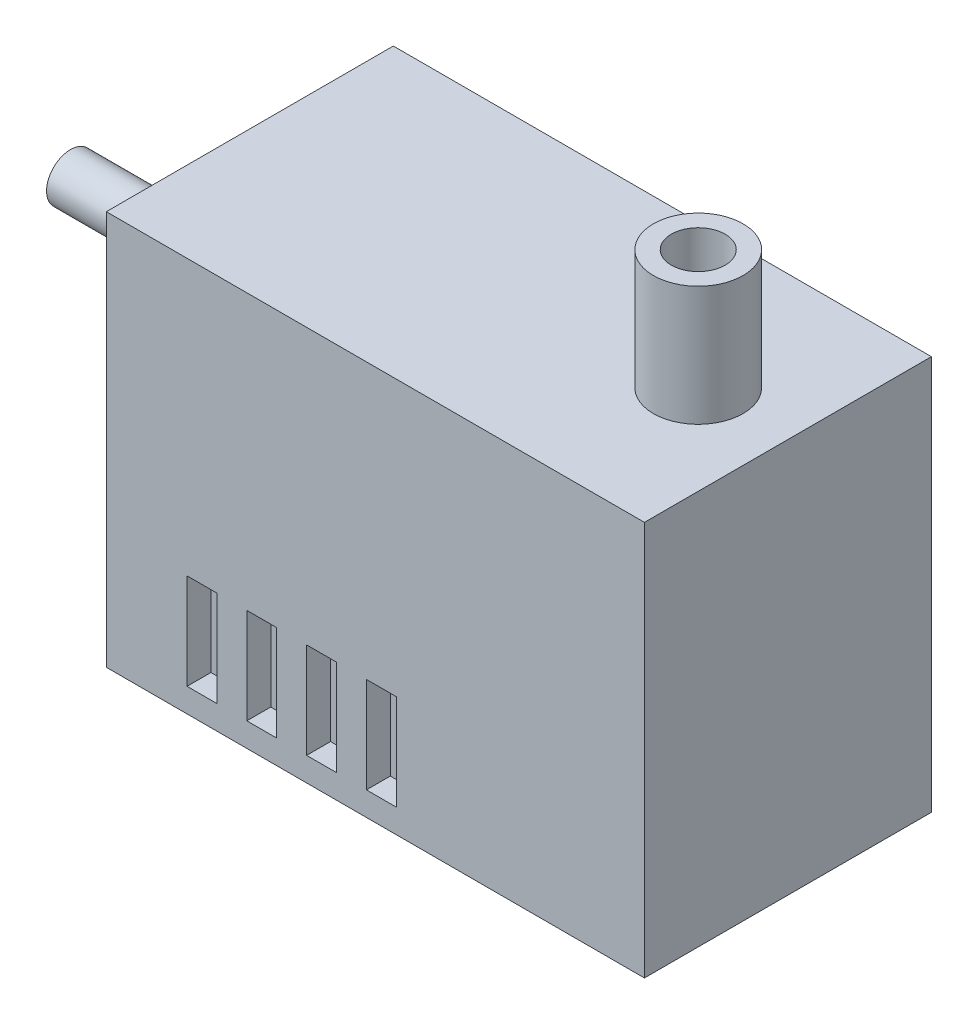
SolidWorks part; units mm, degrees
material "ABS"
ref_plane "Front Plane" through (0, 0, 0) normal (0, 0, 1) x (1, 0, 0)
ref_plane "Top Plane" through (0, 0, 0) normal (0, 1, 0) x (1, 0, 0)
ref_plane "Right Plane" through (0, 0, 0) normal (1, 0, 0) x (0, 0, -1)
other "Configuration Table"
sketch "Sketch1" plane through (0, 0, 0) normal (0, 1, 0) x (1, 0, 0)
  line L1 (-22.5, -12) -> (22.5, -12)
  line L2 (-22.5, -12) -> (-22.5, 12)
  line L3 (-22.5, 12) -> (22.5, 12)
  line L4 (22.5, -12) -> (22.5, 12)
  line L5 (-22.5, -12) -> (22.5, 12) construction
  line L6 (-22.5, 12) -> (22.5, -12) construction
  point P6 (0, 0)
  dimension "D1" = 45
  dimension "D2" = 24
extrude "Pump_Body" add sketch "Sketch1" along normal blind 33
sketch "Sketch2" plane through (0, 0, 0) normal (0, 1, 0) x (1, 0, 0)
  circle A0 centre (15, 0) radius 3.75
  dimension "D1" = 7.5
extrude "Outlet" add sketch "Sketch2" along normal blind 10 from offset 33
sketch "Sketch3" plane through (0, 0, 0) normal (0, 1, 0) x (1, 0, 0)
  circle A0 centre (15, 0) radius 2.25
  dimension "D1" = 4.5
extrude "Outlet_Bore" cut sketch "Sketch3" against normal blind 15 from offset 43
sketch "Sketch4" plane through (0, 0, 0) normal (0, 0, 1) x (1, 0, 0)
  line L0 (-15.75, 2) -> (-13.25, 2)
  line L1 (-13.25, 2) -> (-13.25, 10)
  line L2 (-13.25, 10) -> (-15.75, 10)
  line L3 (-15.75, 10) -> (-15.75, 2)
  line L4 (-10.75, 2) -> (-8.25, 2)
  line L5 (-8.25, 2) -> (-8.25, 10)
  line L6 (-8.25, 10) -> (-10.75, 10)
  line L7 (-10.75, 10) -> (-10.75, 2)
  line L8 (-5.75, 2) -> (-3.25, 2)
  line L9 (-3.25, 2) -> (-3.25, 10)
  line L10 (-3.25, 10) -> (-5.75, 10)
  line L11 (-5.75, 10) -> (-5.75, 2)
  line L12 (-0.75, 2) -> (1.75, 2)
  line L13 (1.75, 2) -> (1.75, 10)
  line L14 (1.75, 10) -> (-0.75, 10)
  line L15 (-0.75, 10) -> (-0.75, 2)
extrude "Inlet_Slots" cut sketch "Sketch4" against normal blind 2 from offset 12
sketch "Sketch5" plane through (0, 0, 0) normal (1, 0, 0) x (0, 0, -1)
  circle A0 centre (0, 22) radius 2
  dimension "D1" = 4
extrude "Cable_Stub" add sketch "Sketch5" along normal blind 15 from offset 37.5
equation "\"Jar_OD\"= 90  'ASSUMED - Part G fallback - jar outer diameter"
equation "\"Jar_H\"= 120  'ASSUMED - Part G fallback - jar height"
equation "\"Pump_L\"= 45  'ASSUMED - Part G fallback"
equation "\"Pump_W\"= 24  'ASSUMED - Part G fallback"
equation "\"Pump_H\"= 33  'ASSUMED - Part G fallback"
equation "\"Pump_Outlet_OD\"= 7.5  'ASSUMED - Part G fallback"
equation "\"Tube_OD\"= 8  'ASSUMED - Part G fallback"
equation "\"Tube_ID\"= 6  'ASSUMED - Part G fallback"
equation "\"TDS_Body_Dia\"= 12  'ASSUMED - Part G fallback"
equation "\"TDS_Wet_Len\"= 45  'ASSUMED - Part G fallback - length in water"
equation "\"DS_Tube_Dia\"= 6  'ASSUMED - Part G fallback"
equation "\"DS_Tube_Len\"= 50  'ASSUMED - Part G fallback"
equation "\"ORP_Body_Dia\"= 12  'ASSUMED - Part G fallback"
equation "\"ORP_Body_Len\"= 150  'ASSUMED - Part G fallback"
equation "\"ORP_Cap_Dia\"= 16  'ASSUMED - Part G fallback"
equation "\"Turb_W\"= 33  'ASSUMED - Part G fallback - head width"
equation "\"Turb_D\"= 28  'ASSUMED - Part G fallback - head depth"
equation "\"Turb_H\"= 30  'ASSUMED - Part G fallback - head height"
equation "\"Turb_Slot_W\"= 10  'ASSUMED - Part G fallback - slot width"
equation "\"Flow_L\"= 62  'ASSUMED - Part G fallback YF-S201"
equation "\"Flow_W\"= 36  'ASSUMED - Part G fallback"
equation "\"Flow_H\"= 35  'ASSUMED - Part G fallback"
equation "\"Thread_G12_OD\"= 20.955  'ASSUMED - Part G fallback thread G1/2 (major diameter)"
equation "\"Valve_L\"= 75  'ASSUMED - Part G fallback"
equation "\"Valve_W\"= 45  'ASSUMED - Part G fallback"
equation "\"Valve_H\"= 60  'ASSUMED - Part G fallback"
equation "\"Tee_L\"= 40  'ASSUMED - Part G fallback - overall length"
equation "\"Tee_Branch_L\"= 25  'ASSUMED - Part G fallback"
equation "\"Tee_OD\"= 12  'ASSUMED - Part G fallback"
equation "\"Cuv_W\"= 12.5  'ASSUMED - old R3 cuvette (station suppressed in SS4)"
equation "\"Cuv_D\"= 12.5  'ASSUMED - old R3 cuvette (station suppressed in SS4)"
equation "\"Cuv_H\"= 45  'ASSUMED - old R3 cuvette (station suppressed in SS4)"
equation "\"LED_Board_L\"= 20  'ASSUMED - Part G fallback"
equation "\"LED_Board_W\"= 20  'ASSUMED - Part G fallback - LED at centre"
equation "\"GUVA_L\"= 20  'ASSUMED - Part G fallback"
equation "\"GUVA_W\"= 12  'ASSUMED - Part G fallback - sensor at centre"
equation "\"Reed_L\"= 27  'ASSUMED - Part G fallback MC-38 half"
equation "\"Reed_W\"= 14  'ASSUMED - Part G fallback"
equation "\"Reed_H\"= 8  'ASSUMED - Part G fallback"
equation "\"ESP_L\"= 51  'ASSUMED - Part G fallback"
equation "\"ESP_W\"= 28  'ASSUMED - Part G fallback"
equation "\"TFT_L\"= 58  'ASSUMED - Part G fallback - board"
equation "\"TFT_W\"= 35  'ASSUMED - Part G fallback - board"
equation "\"TFT_Win_L\"= 35  'ASSUMED - Part G fallback - visible window"
equation "\"TFT_Win_W\"= 28  'ASSUMED - Part G fallback - visible window"
equation "\"Relay_L\"= 50  'ASSUMED - Part G fallback"
equation "\"Relay_W\"= 26  'ASSUMED - Part G fallback"
equation "\"Relay_H\"= 19  'ASSUMED - Part G fallback"
equation "\"Mosfet_L\"= 34  'ASSUMED - Part G fallback"
equation "\"Mosfet_W\"= 17  'ASSUMED - Part G fallback"
equation "\"Mosfet_H\"= 12  'ASSUMED - Part G fallback"
equation "\"TDS_Board_L\"= 42  'ASSUMED - Part G fallback"
equation "\"TDS_Board_W\"= 32  'ASSUMED - Part G fallback"
equation "\"Turb_Board_L\"= 38  'ASSUMED - Part G fallback"
equation "\"Turb_Board_W\"= 28  'ASSUMED - Part G fallback"
equation "\"BNC_Thread_Dia\"= 9.5  'ASSUMED - Part G fallback"
equation "\"Plate_L\"= 420  'ASSUMED - Part G fallback"
equation "\"Plate_W\"= 297  'ASSUMED - Part G fallback"
equation "\"Plate_T\"= 6  'ASSUMED - Part G fallback"
equation "\"Probe_Clr\"= 0.3  'DESIGN VALUE - Part C rule 3 - printed probe hole = diameter + 0.3"
equation "\"Cuv_Clr\"= 0.2  'DESIGN VALUE - Part C rule 3 - cuvette pocket = size + 0.2"
equation "\"Label_H\"= 0.6  'DESIGN VALUE - Part D - raised label height"
equation "\"D1@Sketch1\" = \"Pump_L\""
equation "\"D2@Sketch1\" = \"Pump_W\""
equation "\"D1@Pump_Body\" = \"Pump_H\""
equation "\"D1@Sketch2\" = \"Pump_Outlet_OD\""
equation "\"Booster_L\"= 150  'ASSUMED - Part G fallback - booster pump"
equation "\"Booster_W\"= 95  'ASSUMED - Part G fallback"
equation "\"Booster_H\"= 100  'ASSUMED - Part G fallback"
equation "\"PTube_OD\"= 6.35  'ASSUMED - Part G fallback - product tube 1/4 inch"
equation "\"Qz_Out\"= 12  'ASSUMED - Part G fallback - quartz channel outside square"
equation "\"Qz_Path\"= 10  'ASSUMED - Part G fallback - quartz channel inside light path"
equation "\"Qz_L\"= 40  'ASSUMED - Part G fallback - quartz channel length"
equation "\"LED860_Dia\"= 5  'ASSUMED - Part G fallback - 860 nm LED"
equation "\"BPW_L\"= 5.4  'ASSUMED - Part G fallback - BPW34"
equation "\"BPW_W\"= 4.3  'ASSUMED - Part G fallback - BPW34"
equation "\"Cart_Dia\"= 50  'ASSUMED - Part G fallback - sediment and pre-carbon cartridges"
equation "\"Cart_L\"= 255  'ASSUMED - Part G fallback"
equation "\"UF_Dia\"= 50  'ASSUMED - Part G fallback - UF cartridge"
equation "\"UF_L\"= 260  'ASSUMED - Part G fallback"
equation "\"RO_Dia\"= 62  'ASSUMED - Part G fallback - RO membrane housing"
equation "\"RO_L\"= 300  'ASSUMED - Part G fallback"
equation "\"UVC_Dia\"= 40  'ASSUMED - Part G fallback - UV-C chamber"
equation "\"UVC_L\"= 300  'ASSUMED - Part G fallback"
equation "\"Tank_W\"= 260  'ASSUMED - Part G fallback - storage tank"
equation "\"Tank_D\"= 160  'ASSUMED - Part G fallback"
equation "\"Tank_H\"= 300  'ASSUMED - Part G fallback"
equation "\"Cab_W\"= 400  'ASSUMED - Part G fallback - purifier cabinet"
equation "\"Cab_D\"= 270  'ASSUMED - Part G fallback"
equation "\"Cab_H\"= 560  'ASSUMED - Part G fallback"
equation "\"ORP_Board_L\"= 40  'ASSUMED - Part G fallback - ORP buffer board"
equation "\"ORP_Board_W\"= 30  'ASSUMED - Part G fallback"
equation "\"Opt_Board_L\"= 50  'ASSUMED - Part G fallback - optical front-end board"
equation "\"Opt_Board_W\"= 40  'ASSUMED - Part G fallback"
equation "\"Buck_L\"= 43  'ASSUMED - Part G fallback - 12 V to 5 V buck module"
equation "\"Buck_W\"= 21  'ASSUMED - Part G fallback"
equation "\"Buck_H\"= 14  'ASSUMED - Part G fallback"
equation "\"BB_L\"= 165  'ASSUMED - Part G fallback - breadboard (As_Built_R3 only)"
equation "\"BB_W\"= 55  'ASSUMED - Part G fallback"
equation "\"BB_H\"= 10  'ASSUMED - Part G fallback"
